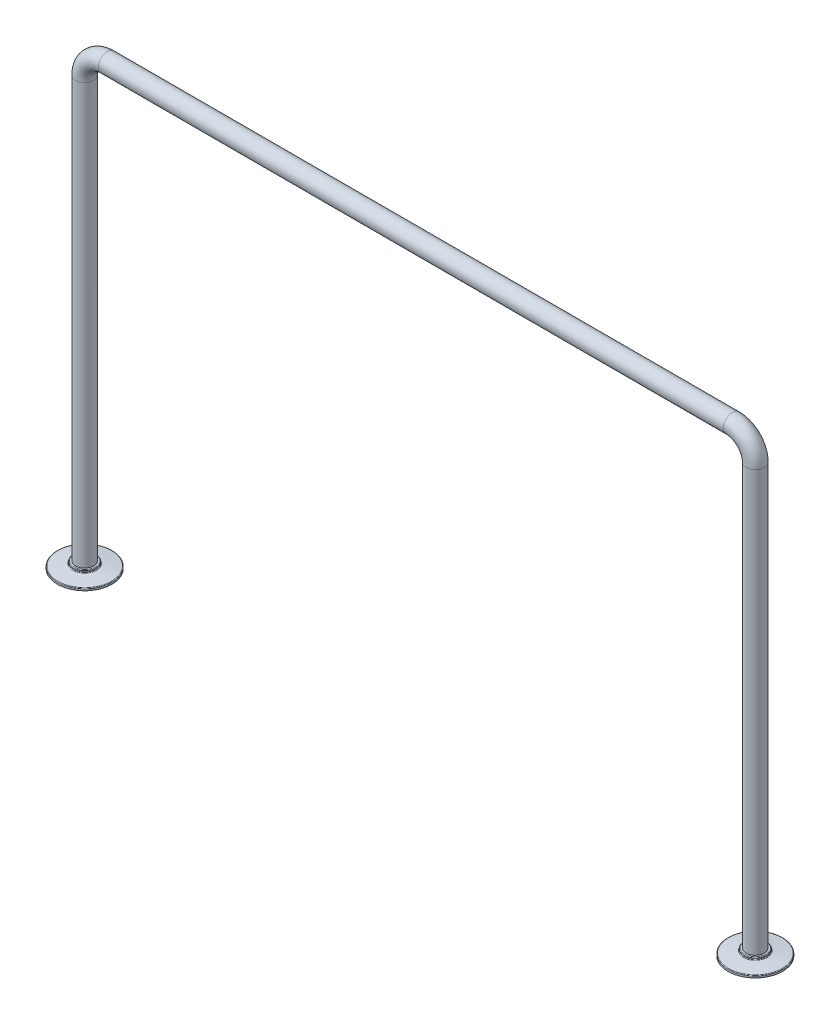
SolidWorks part; units mm, degrees
ref_plane "Front Plane" through (0, 0, 0) normal (0, 0, 1) x (1, 0, 0)
ref_plane "Top Plane" through (0, 0, 0) normal (0, 1, 0) x (1, 0, 0)
ref_plane "Right Plane" through (0, 0, 0) normal (1, 0, 0) x (0, 0, -1)
sketch "Sketch1" plane through (0, 0, 0) normal (0, 0, 1) x (1, 0, 0)
  line L0 (-147.5, 0) -> (-147.5, 185)
  line L1 (-137.5, 195) -> (137.5, 195)
  line L2 (147.5, 185) -> (147.5, 0)
  line L3 (0, 0) -> (0, 195) construction
  arc A0 (137.5, 195) -> (147.5, 185) centre (137.5, 185) cw
  arc A1 (-147.5, 185) -> (-137.5, 195) centre (-137.5, 185) cw
  point P7 (0, 0)
  point P10 (147.5, 195)
  point P13 (-147.5, 195)
  dimension "D3" = 10
  dimension "D1" = 195
  dimension "D2" = 295
sketch "Sketch3" plane through (0, 0, 0) normal (0, 1, 0) x (1, 0, 0)
  circle A0 centre (-147.5, 0) radius 4
sweep "Sweep1" add profiles "Sketch3" path "Sketch1"
sketch "Sketch4" plane through (0, 0, 0) normal (0, 0, 1) x (1, 0, 0)
  line L0 (-147.5, 0) -> (-147.5, -9.8653) construction
  line L1 (-151.5, 0) -> (-143.5, 0) construction
  line L2 (-147.5, 0) -> (-147.5, -3)
  line L3 (-147.5, -3) -> (-159.5, -3)
  line L4 (-159.5, -3) -> (-159.5, -2.2602)
  line L5 (-159.2424, -1.9632) -> (-152.7576, -1.0368)
  line L6 (-152.5, -0.7398) -> (-152.5, -0.3)
  line L7 (-152.2, 0) -> (-147.5, 0)
  arc A0 (-159.5, -2.2602) -> (-159.2424, -1.9632) centre (-159.2, -2.2602) cw
  arc A1 (-152.7576, -1.0368) -> (-152.5, -0.7398) centre (-152.8, -0.7398) ccw
  arc A2 (-152.5, -0.3) -> (-152.2, 0) centre (-152.2, -0.3) cw
  point P11 (-159.5, -2)
  point P14 (-152.5, -1)
  point P17 (-152.5, 0)
  dimension "D6" = 0.3
  dimension "D1" = 3
  dimension "D2" = 12
  dimension "D3" = 1
  dimension "D4" = 5
  dimension "D5" = 1
revolve "Revolve1" add sketch "Sketch4" angle 360 about L0
mirror "Mirror1" about plane through (0, 0, 0) normal (1, 0, 0) of "Revolve1"
sketch "Sketch5" plane through (0, 0, 0) normal (0, 0, 1) x (1, 0, 0)
  line L0 (0, 0) -> (0, 215.2759) construction
  line L1 (-137.5, 195) -> (137.5, 195) construction
  circle A0 centre (-100, 195) radius 2
  dimension "D1" = 4
  dimension "D2" = 100
extrude "Cut-Extrude1" cut sketch "Sketch5" against normal blind 10
pattern_linear "LPattern1" count 5 spacing 50 along (1, 0, 0) of "Cut-Extrude1"
